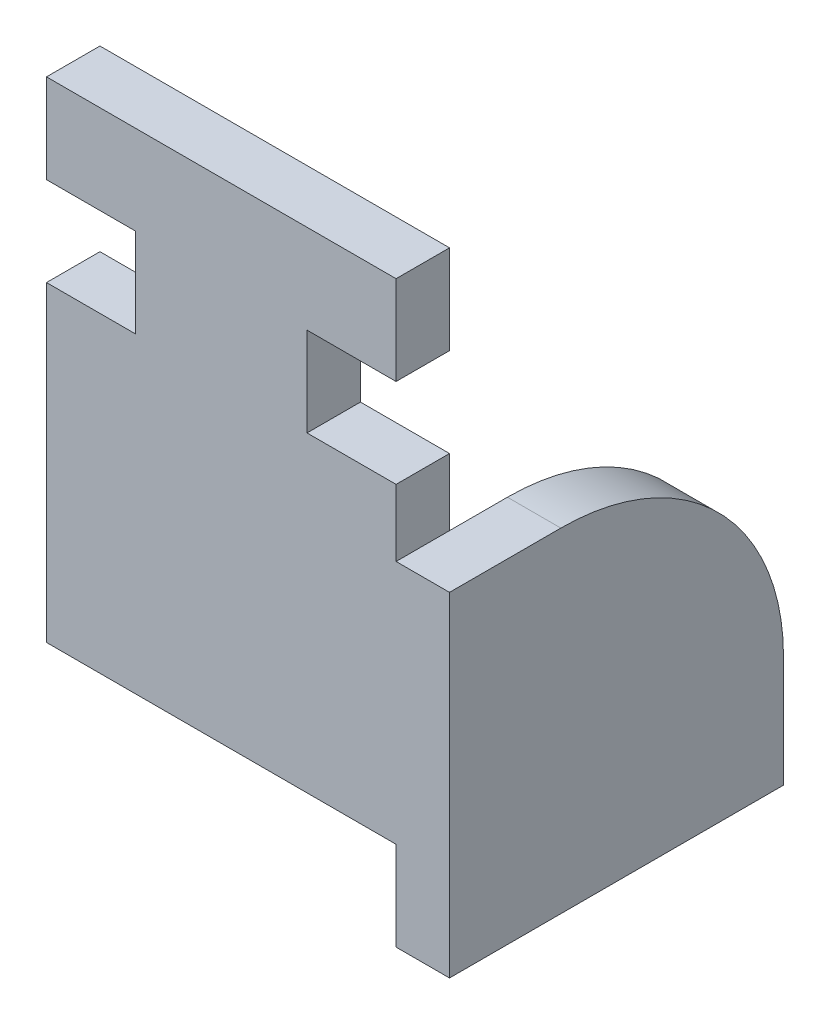
SolidWorks part; units mm, degrees
material "PBT General Purpose"
ref_plane "Front Plane" through (0, 0, 0) normal (0, 0, 1) x (1, 0, 0)
ref_plane "Top Plane" through (0, 0, 0) normal (0, 1, 0) x (1, 0, 0)
ref_plane "Right Plane" through (0, 0, 0) normal (1, 0, 0) x (0, 0, -1)
sketch "Sketch1" plane through (0, 0, 0) normal (0, 0, 1) x (1, 0, 0)
  line L0 (0, 0) -> (0, 1.4)
  line L1 (0, 1.4) -> (0.4, 1.4)
  line L2 (0.4, 1.4) -> (0.4, 1.8)
  line L3 (0.4, 1.8) -> (0, 1.8)
  line L4 (0, 1.8) -> (0, 2.2)
  line L5 (0, 2.2) -> (1.57, 2.2)
  line L6 (1.57, 2.2) -> (1.57, 1.8)
  line L7 (1.57, 1.8) -> (1.17, 1.8)
  line L8 (1.17, 1.8) -> (1.17, 1.4)
  line L9 (1.17, 1.4) -> (1.57, 1.4)
  line L10 (1.57, 1.4) -> (1.57, 0)
  line L11 (1.57, 0) -> (0, 0)
  dimension "D1" = 0.4
  dimension "D2" = 0.4
  dimension "D3" = 0.77
  dimension "D4" = 0.4
  dimension "D5" = 0.4
  dimension "D6" = 1.4
  dimension "D7" = 0.4
extrude "Boss-Extrude1" add sketch "Sketch1" along normal blind 0.24
sketch "Sketch2" plane through (1.57, 0, 0) normal (1, 0, 0) x (0, 0, -1)
  line L0 (-0.24, 1.4) -> (0, 1.4) construction
  line L1 (-0.24, -0.4) -> (1.26, -0.4)
  line L2 (-0.24, -0.4) -> (-0.24, 1.1)
  line L3 (-0.24, 1.1) -> (1.26, 1.1)
  line L4 (1.26, -0.4) -> (1.26, 1.1)
  line L5 (-0.24, 0) -> (-0.24, 1.4) construction
  dimension "D1" = 0.3
  dimension "D2" = 1.5
  dimension "D3" = 1.5
extrude "Boss-Extrude2" add sketch "Sketch2" along normal blind 0.24 contours L3 L4 L1 L2
fillet "Fillet1" radius 1 1 edges at (1.69, 1.1, -1.26)
